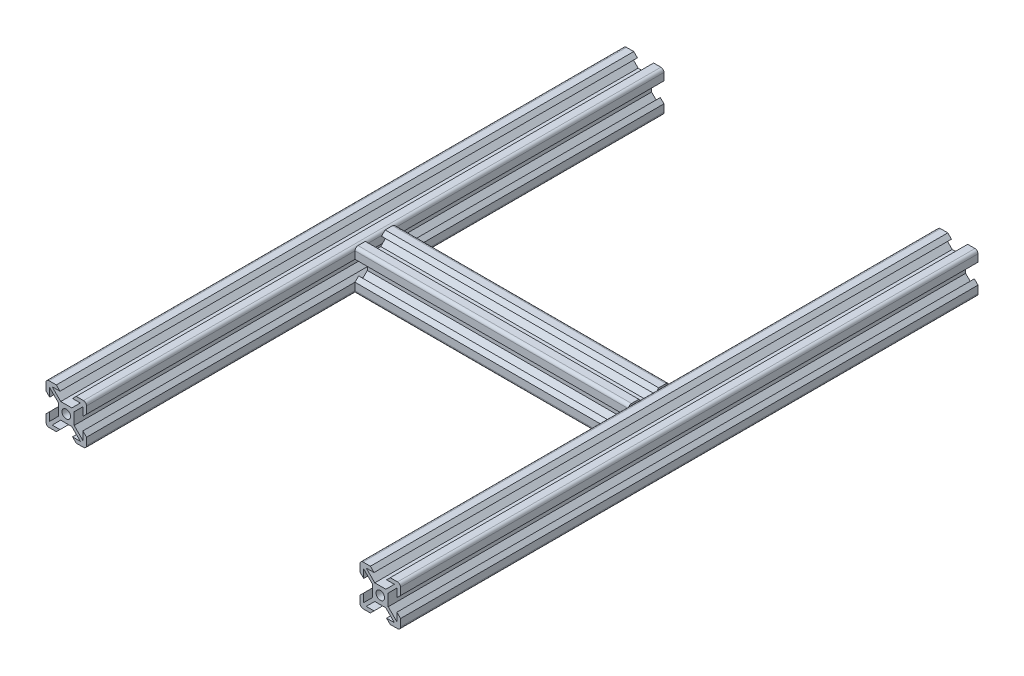
SolidWorks part; units mm, degrees
material "6061-T6 (SS)"
ref_plane "Front Plane" through (0, 0, 0) normal (0, 0, 1) x (1, 0, 0)
ref_plane "Top Plane" through (0, 0, 0) normal (0, 1, 0) x (1, 0, 0)
ref_plane "Right Plane" through (0, 0, 0) normal (1, 0, 0) x (0, 0, -1)
sketch "Sketch1" plane through (0, 0, 0) normal (0, 1, 0) x (1, 0, 0)
  line L0 (77.5, 0) -> (-77.5, 0)
  line L1 (-77.5, 142.5) -> (-77.5, -142.5)
  line L2 (77.5, 142.5) -> (77.5, -142.5)
  point P8 (0, 0)
  dimension "D1" = 285
  dimension "D2" = 142.5
  dimension "D3" = 155
other "Aluminium extrusion 2020(1)"
ref_plane "Plane1" through (-77.5, 0, -142.5) normal (0, 0, 1) x (1, 0, 0)
sketch "Sketch11" plane through (-77.5, 0, -142.5) normal (0, 0, 1) x (1, 0, 0)
  line L21 (-2.7315, 3.9807) -> (-6.9509, 8.2)
  line L29 (-4.9, 10) -> (-8.5, 10)
  line L44 (-10, 4.9) -> (-10, 8.5)
  line L49 (-3.1, 8.2) -> (-4.9, 10)
  line L50 (-8.2, 7.2193) -> (-3.9007, 2.92)
  line L51 (-3.9007, 2.92) -> (-3.9007, -2.92)
  line L52 (-2.7315, 3.9807) -> (2.7315, 3.9807)
  line L54 (-3.1, 8.2) -> (-6.9509, 8.2)
  line L56 (-8.2, 3.1) -> (-8.2, 7.2193)
  line L57 (-8.2, 3.1) -> (-10, 4.9)
  line L58 (8.2, 3.1) -> (10, 4.9)
  line L59 (8.2, 3.1) -> (8.2, 7.2193)
  line L60 (3.1, 8.2) -> (6.9509, 8.2)
  line L61 (3.9007, 2.92) -> (3.9007, -2.92)
  line L62 (8.2, 7.2193) -> (3.9007, 2.92)
  line L63 (3.1, 8.2) -> (4.9, 10)
  line L64 (10, 4.9) -> (10, 8.5)
  line L65 (4.9, 10) -> (8.5, 10)
  line L67 (2.7315, 3.9807) -> (6.9509, 8.2)
  line L68 (2.7315, -3.9807) -> (6.9509, -8.2)
  line L69 (4.9, -10) -> (8.5, -10)
  line L70 (10, -4.9) -> (10, -8.5)
  line L71 (3.1, -8.2) -> (4.9, -10)
  line L72 (8.2, -7.2193) -> (3.9007, -2.92)
  line L73 (3.1, -8.2) -> (6.9509, -8.2)
  line L74 (8.2, -3.1) -> (8.2, -7.2193)
  line L75 (8.2, -3.1) -> (10, -4.9)
  line L76 (-8.2, -3.1) -> (-10, -4.9)
  line L77 (-8.2, -3.1) -> (-8.2, -7.2193)
  line L78 (-3.1, -8.2) -> (-6.9509, -8.2)
  line L79 (-2.7315, -3.9807) -> (2.7315, -3.9807)
  line L80 (-8.2, -7.2193) -> (-3.9007, -2.92)
  line L81 (-3.1, -8.2) -> (-4.9, -10)
  line L82 (-10, -4.9) -> (-10, -8.5)
  line L83 (-4.9, -10) -> (-8.5, -10)
  line L84 (-2.7315, -3.9807) -> (-6.9509, -8.2)
  circle A6 centre (0, 0) radius 2.1
  arc A7 (-10, -8.5) -> (-8.5, -10) centre (-8.5, -8.5) ccw
  arc A8 (8.5, -10) -> (10, -8.5) centre (8.5, -8.5) ccw
  arc A9 (10, 8.5) -> (8.5, 10) centre (8.5, 8.5) ccw
  arc A10 (-8.5, 10) -> (-10, 8.5) centre (-8.5, 8.5) ccw
  point P46 (0, 0)
  dimension "D1" = 1.5
equation "\"D2@Sketch1\"=\"D1@Sketch1\"/2"
